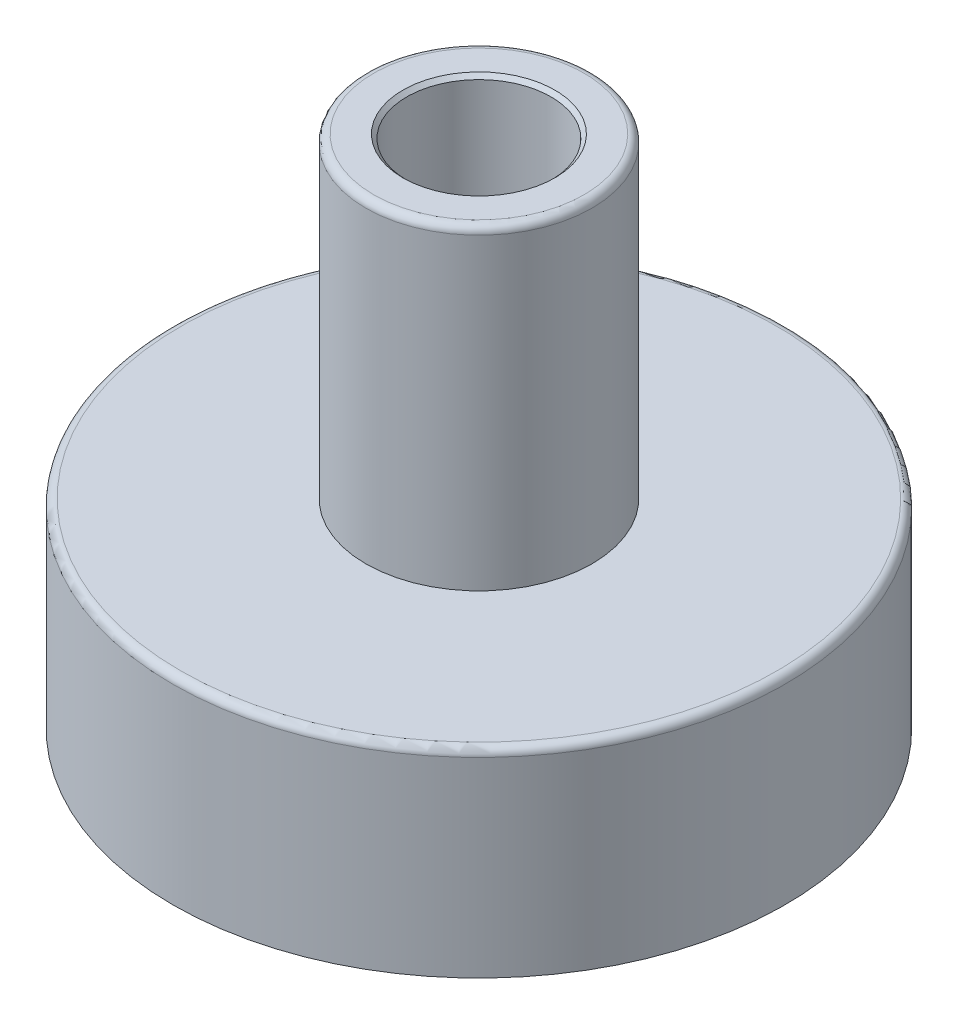
SolidWorks part; units mm, degrees
ref_plane "Front Plane" through (0, 0, 0) normal (0, 0, 1) x (1, 0, 0)
ref_plane "Top Plane" through (0, 0, 0) normal (0, 1, 0) x (1, 0, 0)
ref_plane "Right Plane" through (0, 0, 0) normal (1, 0, 0) x (0, 0, -1)
sketch "Sketch1" plane through (0, 0, 0) normal (0, 1, 0) x (1, 0, 0)
  circle A0 centre (0, 0) radius 7.85
  dimension "D1" = 15.7
extrude "Boss-Extrude1" add sketch "Sketch1" against normal blind 5.1
sketch "Sketch2" plane through (0, 0, 0) normal (0, 1, 0) x (1, 0, 0)
  circle A0 centre (0, 0) radius 2.9
  dimension "D1" = 5.8
extrude "Boss-Extrude2" add sketch "Sketch2" along normal blind 8.1
sketch "Sketch3" plane through (0, 8.1, 0) normal (0, 1, 0) x (1, 0, 0)
  circle A0 centre (0, 0) radius 1.85
  dimension "D1" = 3.7
extrude "Cut-Extrude1" cut sketch "Sketch3" against normal blind 7
chamfer "Chamfer1" distance 0.1 angle 45 1 edges at (0, 8.1, 1.85)
fillet "Fillet2" radius 0.2 2 edges at (0, 0, 7.85) (0, 8.1, 2.9)
sketch "Sketch4" plane through (0, -5.1, 0) normal (0, -1, 0) x (1, 0, 0)
  circle A0 centre (0, 0) radius 6
  circle A2 centre (0, 0) radius 6.25
  dimension "D1" = 12
  dimension "D2" = 12.5
extrude "Cut-Extrude2" cut sketch "Sketch4" against normal blind 0.25
